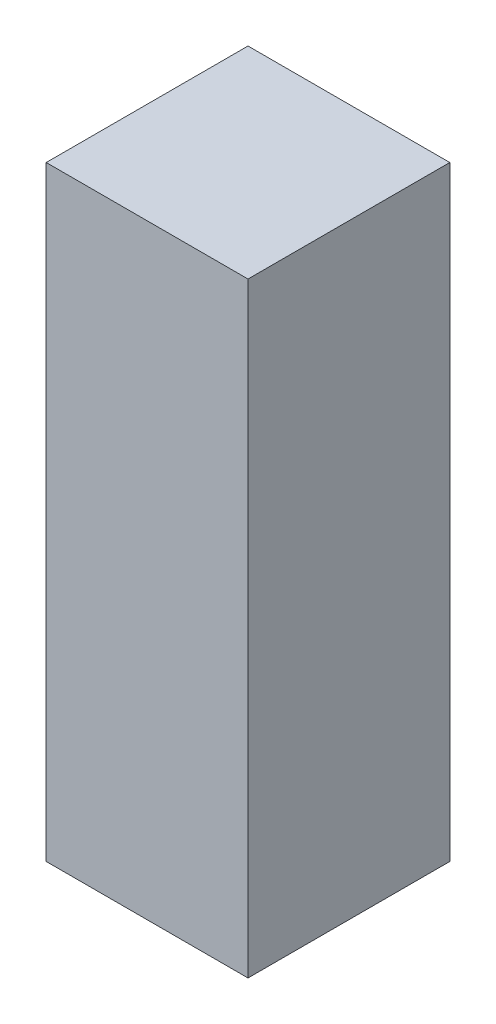
SolidWorks part; units mm, degrees
ref_plane "前视基准面" through (0, 0, 0) normal (0, 0, 1) x (1, 0, 0)
ref_plane "上视基准面" through (0, 0, 0) normal (0, 1, 0) x (1, 0, 0)
ref_plane "右视基准面" through (0, 0, 0) normal (1, 0, 0) x (0, 0, -1)
sketch "草图1" plane through (0, 0, 0) normal (0, 1, 0) x (1, 0, 0)
  line L1 (0, 0) -> (25, 0)
  line L2 (0, 0) -> (0, 25)
  line L3 (0, 25) -> (25, 25)
  line L4 (25, 0) -> (25, 25)
extrude "凸台-拉伸1" add sketch "草图1" along normal blind 75
